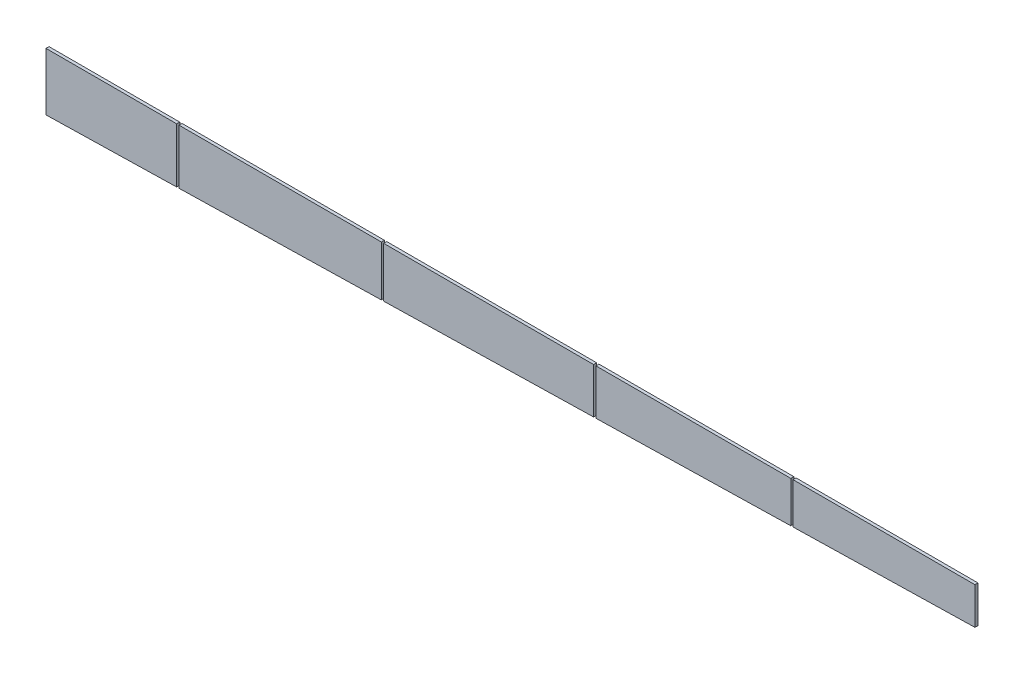
SolidWorks part; units mm, degrees
ref_plane "前视基准面" through (0, 0, 0) normal (0, 0, 1) x (1, 0, 0)
ref_plane "上视基准面" through (0, 0, 0) normal (0, 1, 0) x (1, 0, 0)
ref_plane "右视基准面" through (0, 0, 0) normal (1, 0, 0) x (0, 0, -1)
sketch "草图1" plane through (0, 0, 0) normal (0, 0, 1) x (1, 0, 0)
  line L0 (9.043, 42.7522) -> (9.043, 4.7341)
  line L1 (9.043, 4.7341) -> (95.2683, 6.6523)
  line L2 (95.2683, 6.6523) -> (95.2683, 42.7522)
  line L3 (95.2683, 42.7522) -> (9.043, 42.7522)
  line L4 (96.7683, 42.7522) -> (96.7683, 6.6857)
  line L5 (96.7683, 6.6857) -> (230.2683, 9.6555)
  line L6 (230.2683, 9.6555) -> (230.2683, 42.7522)
  line L7 (230.2683, 42.7522) -> (96.7683, 42.7522)
  line L8 (231.7683, 42.7522) -> (370.2683, 42.7522)
  line L9 (370.2683, 42.7522) -> (370.2683, 12.77)
  line L10 (370.2683, 12.77) -> (231.7683, 9.6889)
  line L11 (231.7683, 9.6889) -> (231.7683, 42.7522)
  line L12 (371.7683, 42.7522) -> (371.7683, 12.8033)
  line L13 (371.7683, 12.8033) -> (500.2683, 15.662)
  line L14 (500.2683, 15.662) -> (500.2683, 42.7522)
  line L15 (500.2683, 42.7522) -> (371.7683, 42.7522)
  line L16 (501.7683, 42.7522) -> (501.7683, 15.6953)
  line L17 (501.7683, 15.6953) -> (621.7683, 18.3649)
  line L18 (621.7683, 18.3649) -> (621.7683, 42.7522)
  line L19 (621.7683, 42.7522) -> (501.7683, 42.7522)
extrude "凸台-拉伸1" add sketch "草图1" along normal blind 2
